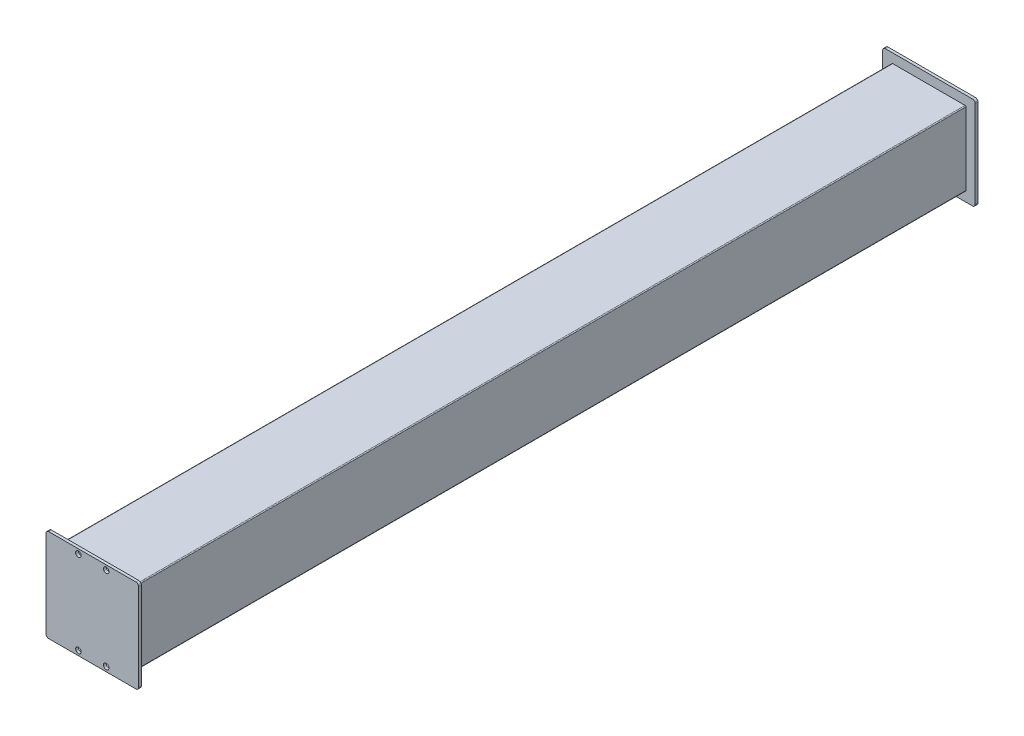
SolidWorks part; units mm, degrees
material "Alloy Steel"
ref_plane "Front Plane" through (0, 0, 0) normal (0, 0, 1) x (1, 0, 0)
ref_plane "Top Plane" through (0, 0, 0) normal (0, 1, 0) x (1, 0, 0)
ref_plane "Right Plane" through (0, 0, 0) normal (1, 0, 0) x (0, 0, -1)
sketch "Sketch2" plane through (0, 0, 0) normal (0, 0, 1) x (1, 0, 0)
  line L0 (-36.4, 36.4) -> (36.4, 36.4)
  line L1 (-40, -40) -> (40, -40)
  line L2 (-40, -40) -> (-40, 40)
  line L3 (-40, 40) -> (40, 40)
  line L4 (40, -40) -> (40, 40)
  line L5 (-40, -40) -> (40, 40) construction
  line L6 (-40, 40) -> (40, -40) construction
  line L7 (36.4, -36.4) -> (36.4, 36.4)
  line L8 (-36.4, -36.4) -> (36.4, -36.4)
  line L9 (-36.4, -36.4) -> (-36.4, 36.4)
  point P0 (0, 0)
  dimension "D1" = 80
  dimension "D2" = 80
  dimension "D3" = 3.6
extrude "Boss-Extrude1" add sketch "Sketch2" along normal blind 900
fillet "Fillet1" radius 1 4 edges at (40, -40, 450) (-40, -40, 450) (40, 40, 450) (-40, 40, 450)
fillet "Fillet2" radius 1 4 edges at (36.4, -36.4, 450) (-36.4, -36.4, 450) (-36.4, 36.4, 450) (36.4, 36.4, 450)
sketch "Sketch3" plane through (0, 0, 900) normal (0, 0, 1) x (1, 0, 0)
  line L1 (-50, -50) -> (50, -50)
  line L2 (-50, -50) -> (-50, 50)
  line L3 (-50, 50) -> (50, 50)
  line L4 (50, -50) -> (50, 50)
  line L5 (-50, -50) -> (50, 50) construction
  line L6 (-50, 50) -> (50, -50) construction
  point P0 (0, 0)
  dimension "D1" = 100
  dimension "D2" = 100
extrude "Boss-Extrude2" add sketch "Sketch3" along normal blind 3
fillet "Fillet3" radius 3 4 edges at (-50, -50, 901.5) (50, -50, 901.5) (50, 50, 901.5) (-50, 50, 901.5)
sketch "Sketch5" plane through (0, 0, 900) normal (0, 0, -1) x (-1, 0, 0)
  line L0 (0, -50) -> (0, 50) construction
  line L1 (47, -50) -> (-47, -50) construction
  line L2 (-47, 50) -> (47, 50) construction
  line L3 (-50, 0) -> (50, 0) construction
  line L4 (-50, -47) -> (-50, 47) construction
  line L5 (50, 47) -> (50, -47) construction
  circle A0 centre (15, -45) radius 3
  circle A1 centre (-15, -45) radius 3
  circle A2 centre (15, 45) radius 3
  circle A3 centre (-15, 45) radius 3
  dimension "D1" = 5
  dimension "D2" = 5
  dimension "D3" = 6
  dimension "D4" = 15
  dimension "D5" = 15
extrude "Cut-Extrude1" cut sketch "Sketch5" against normal up to surface (3 mm away) up to face at (0, 0, 903)
sketch "Sketch6" plane through (0, 0, 0) normal (0, 0, -1) x (-1, 0, 0)
  line L1 (-50, -50) -> (50, -50)
  line L2 (-50, -50) -> (-50, 50)
  line L3 (-50, 50) -> (50, 50)
  line L4 (50, -50) -> (50, 50)
  line L5 (-50, -50) -> (50, 50) construction
  line L6 (-50, 50) -> (50, -50) construction
  point P0 (0, 0)
  dimension "D1" = 100
  dimension "D2" = 100
extrude "Boss-Extrude3" add sketch "Sketch6" along normal blind 3
fillet "Fillet4" radius 3 4 edges at (50, -50, -1.5) (-50, -50, -1.5) (-50, 50, -1.5) (50, 50, -1.5)
